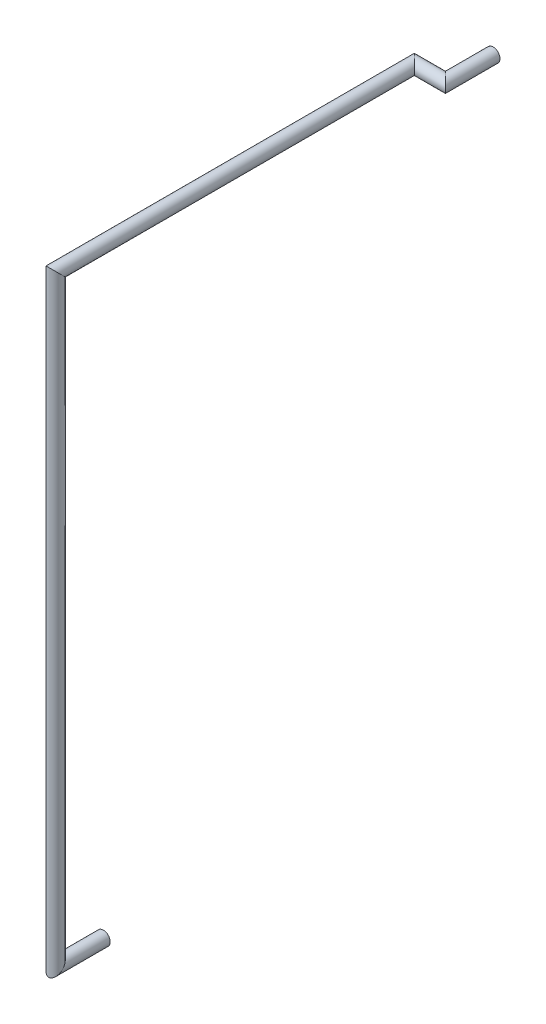
SolidWorks part; units mm, degrees
ref_plane "Plan de face" through (0, 0, 0) normal (1, 0, 0) x (0, 1, 0)
ref_plane "Plan de dessus" through (0, 0, 0) normal (0, 0, 1) x (0, 1, 0)
ref_plane "Plan de droite" through (0, 0, 0) normal (0, 1, 0) x (-1, 0, 0)
sketch3d "Esquisse3D1"
  line L0 (0, 0, 0) -> (0, 0, 3.5)
  line L1 (0, 0, 3.5) -> (0, 44.06, 3.5)
  line L2 (0, 44.06, 3.5) -> (0, 44.06, -22.79)
  line L3 (0, 44.06, -22.79) -> (2.28, 44.06, -22.79)
  line L4 (2.28, 44.06, -22.79) -> (2.28, 44.06, -26.29)
  dimension "D1" = 3.5
  dimension "D2" = 3.5
  dimension "D3" = 2.28
  dimension "D4" = 26.29
  dimension "D5" = 44.06
sketch "Esquisse1" plane through (0, 0, 0) normal (0, 0, 1) x (0, 1, 0)
  circle A0 centre (0, 0) radius 0.5
  dimension "D1" = 1
sweep "Balayage1" add profiles "Esquisse1" path "Esquisse3D1"
